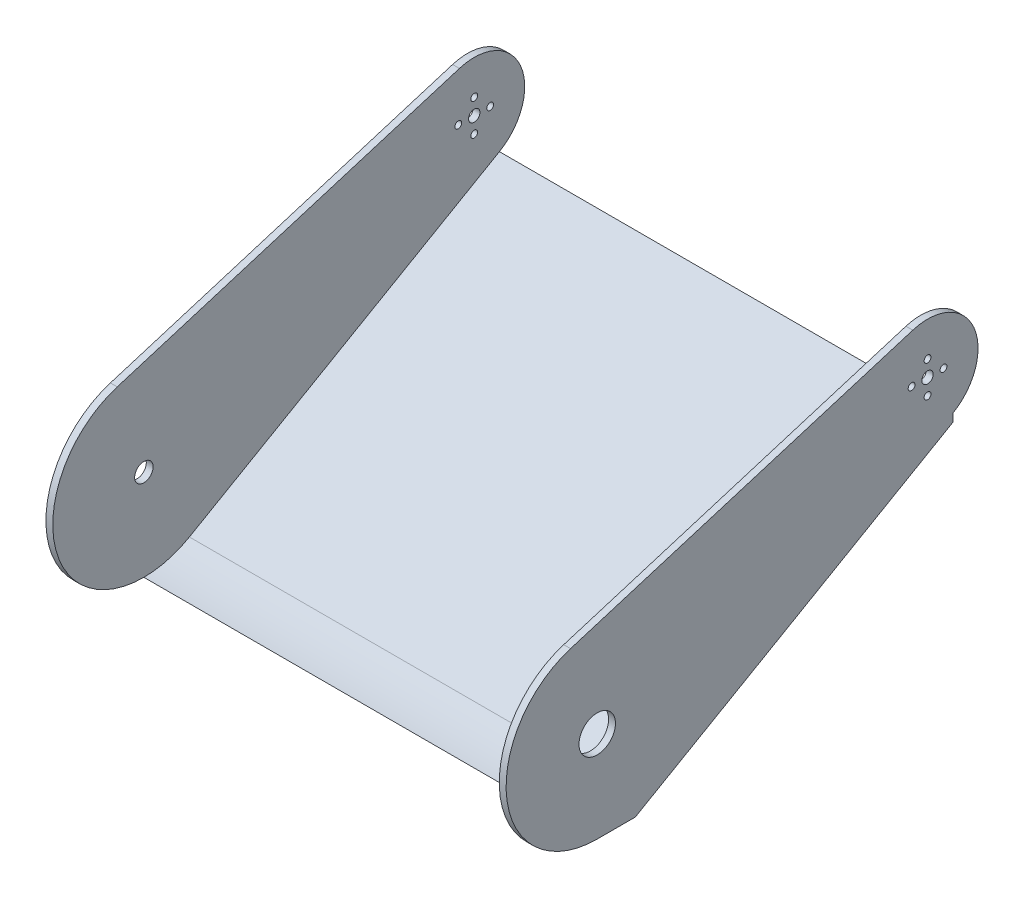
SolidWorks part; units mm, degrees
ref_plane "前视基准面" through (0, 0, 0) normal (0, 0, 1) x (1, 0, 0)
ref_plane "上视基准面" through (0, 0, 0) normal (0, 1, 0) x (1, 0, 0)
ref_plane "右视基准面" through (0, 0, 0) normal (1, 0, 0) x (0, 0, -1)
sketch "草图2" plane through (0, 0, 0) normal (1, 0, 0) x (0, 0, -1)
  line L0 (-11.7006, 38.2504) -> (138.5148, 84.2007)
  line L1 (0, -40) -> (16.7102, -40)
  line L2 (16.7102, -40) -> (120, 19.5373)
  line L3 (156.0716, 43.7921) -> (120, 23)
  line L4 (120, 23) -> (19.9756, -34.6551)
  line L6 (120, 19.5373) -> (156.0716, 40.3294)
  line L7 (156.0716, 43.7921) -> (156.0716, 40.3294)
  circle A0 centre (0, 0) radius 40
  circle A1 centre (145, 63) radius 2.5
  circle A2 centre (145, 63) radius 22.1704
  circle A3 centre (0, 0) radius 3
  circle A4 centre (145, 70) radius 1.5
  circle A5 centre (152, 63) radius 1.5
  circle A6 centre (145, 56) radius 1.5
  circle A7 centre (138, 63) radius 1.5
  point P19 (145, 70)
  point P28 (145, 63)
  dimension "D1" = 80
  dimension "D7" = 5
  dimension "D6" = 44.3408
  dimension "D8" = 6
  dimension "D11" = 3
  dimension "D2" = 120
  dimension "D3" = 23
  dimension "D4" = 25
  dimension "D5" = 40
  dimension "D9" = 3
  dimension "D10" = 16.7102
  dimension "D12" = 7
  dimension "D13" = 4
extrude "凸台-拉伸1" add sketch "草图2" along normal blind 3
sketch "草图4" plane through (3, 0, 0) normal (1, 0, 0) x (0, 0, -1)
  line L0 (0, -40) -> (16.7102, -40)
  line L1 (16.7102, -40) -> (156.0716, 40.3294)
  line L2 (156.0716, 40.3294) -> (156.0716, 43.7921)
  line L3 (156.0716, 43.7921) -> (19.9756, -34.6551)
  line L4 (156.0716, 43.7921) -> (156.0716, 40.3294) construction
  arc A0 (0, -40) -> (19.9756, -34.6551) centre (0, 0) ccw
extrude "凸台-拉伸2" add sketch "草图4" along normal blind 196
ref_plane "基准面5" through (101, 0, 0) normal (1, 0, 0) x (0, 0, -1)
mirror "镜向2" about plane through (101, 0, 0) normal (1, 0, 0) of "凸台-拉伸1"
sketch "草图5" plane through (202, 0, 0) normal (1, 0, 0) x (0, 0, -1)
  circle A0 centre (0, 0) radius 8
  dimension "D1" = 16
extrude "切除-拉伸1" cut sketch "草图5" against normal blind 10
sketch "草图6" plane through (0, 0, 0) normal (-1, 0, 0) x (0, 0, 1)
  circle A0 centre (0, 0) radius 4.05
  dimension "D1" = 8.1
extrude "切除-拉伸2" cut sketch "草图6" against normal blind 10
